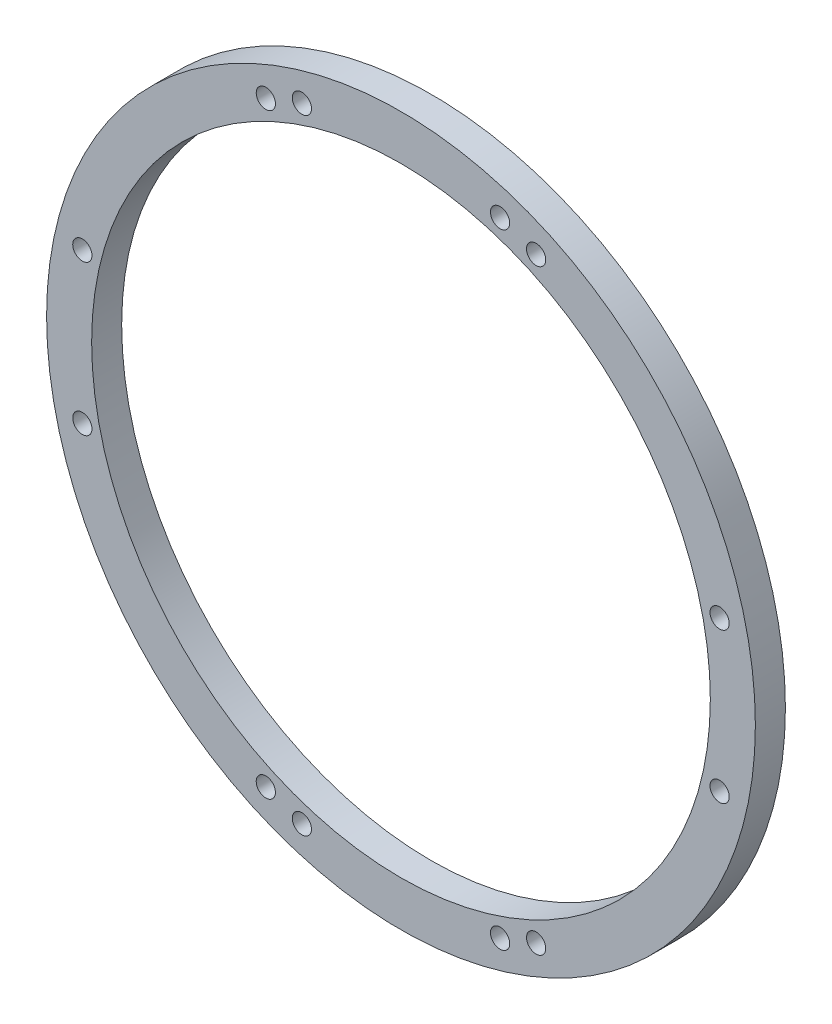
SolidWorks part; units mm, degrees
material "A-玻璃纤维"
ref_plane "前视基准面" through (0, 0, 0) normal (0, 0, 1) x (1, 0, 0)
ref_plane "上视基准面" through (0, 0, 0) normal (0, 1, 0) x (1, 0, 0)
ref_plane "右视基准面" through (0, 0, 0) normal (1, 0, 0) x (0, 0, -1)
sketch "草图1" plane through (0, 0, 0) normal (0, 0, 1) x (1, 0, 0)
  line L0 (0, 0) -> (0, 54.5) construction
  line L1 (0, 51.9423) -> (16.5, 51.9423) construction
  line L2 (0, 49.6387) -> (22.5, 49.6387) construction
  line L3 (0, 0) -> (54.5, 0) construction
  line L4 (53.0471, 0) -> (53.0471, 12.5) construction
  circle A0 centre (0, 0) radius 59
  circle A1 centre (0, 0) radius 51.5
  circle A2 centre (0, 0) radius 54.5 construction
  circle A3 centre (16.5, 51.9423) radius 1.6
  circle A4 centre (22.5, 49.6387) radius 1.6
  circle A5 centre (53.0471, 12.5) radius 1.6
  circle A6 centre (22.5, -49.6387) radius 1.6
  circle A7 centre (16.5, -51.9423) radius 1.6
  circle A8 centre (53.0471, -12.5) radius 1.6
  circle A9 centre (-16.5, -51.9423) radius 1.6
  circle A10 centre (-22.5, -49.6387) radius 1.6
  circle A11 centre (-53.0471, -12.5) radius 1.6
  circle A12 centre (-53.0471, 12.5) radius 1.6
  circle A13 centre (-22.5, 49.6387) radius 1.6
  circle A14 centre (-16.5, 51.9423) radius 1.6
  dimension "D1" = 118
  dimension "D2" = 103
  dimension "D3" = 109
  dimension "D6" = 3.2
  dimension "D7" = 3.2
  dimension "D9" = 3.2
  dimension "D4" = 16.5
  dimension "D5" = 22.5
  dimension "D8" = 12.5
extrude "凸台-拉伸1" add sketch "草图1" along normal blind 5
